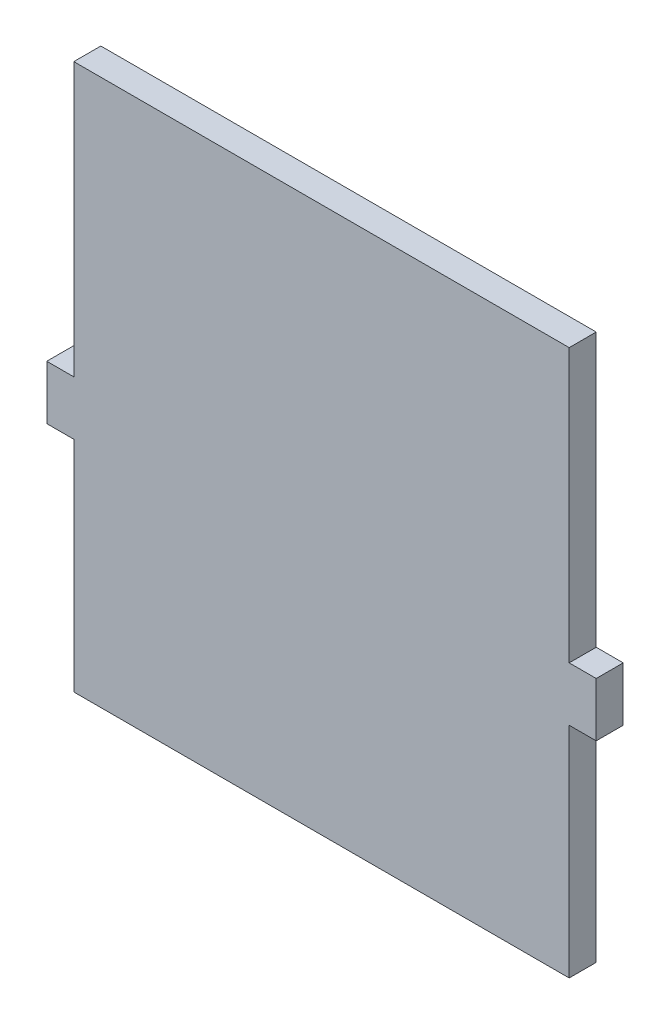
SolidWorks part; units mm, degrees
ref_plane "Přední rovina" through (0, 0, 0) normal (0, 0, 1) x (1, 0, 0)
ref_plane "Horní rovina" through (0, 0, 0) normal (0, 1, 0) x (1, 0, 0)
ref_plane "Pravá rovina" through (0, 0, 0) normal (1, 0, 0) x (0, 0, -1)
sketch "Skica1" plane through (0, 0, 0) normal (0, 0, 1) x (1, 0, 0)
  line L0 (55, -36.31) -> (55, -60.61)
  line L1 (0, 0) -> (55, 0)
  line L2 (0, 0) -> (0, -30.31)
  line L3 (0, -60.61) -> (55, -60.61)
  line L4 (55, 0) -> (55, -30.31)
  line L5 (0, -30.31) -> (-3, -30.31)
  line L6 (0, -36.31) -> (-3, -36.31)
  line L7 (-3, -30.31) -> (-3, -36.31)
  line L8 (55, -30.31) -> (58, -30.31)
  line L9 (55, -36.31) -> (58, -36.31)
  line L10 (58, -30.31) -> (58, -36.31)
  line L11 (0, -36.31) -> (0, -60.61)
  dimension "D1" = 55
  dimension "D2" = 60.61
  dimension "D3" = 30.31
  dimension "D4" = 0
  dimension "D5" = 6
  dimension "D6" = 6
  dimension "D7" = 3
  dimension "D8" = 3
extrude "Přidat vysunutím1" add sketch "Skica1" along normal blind 3
